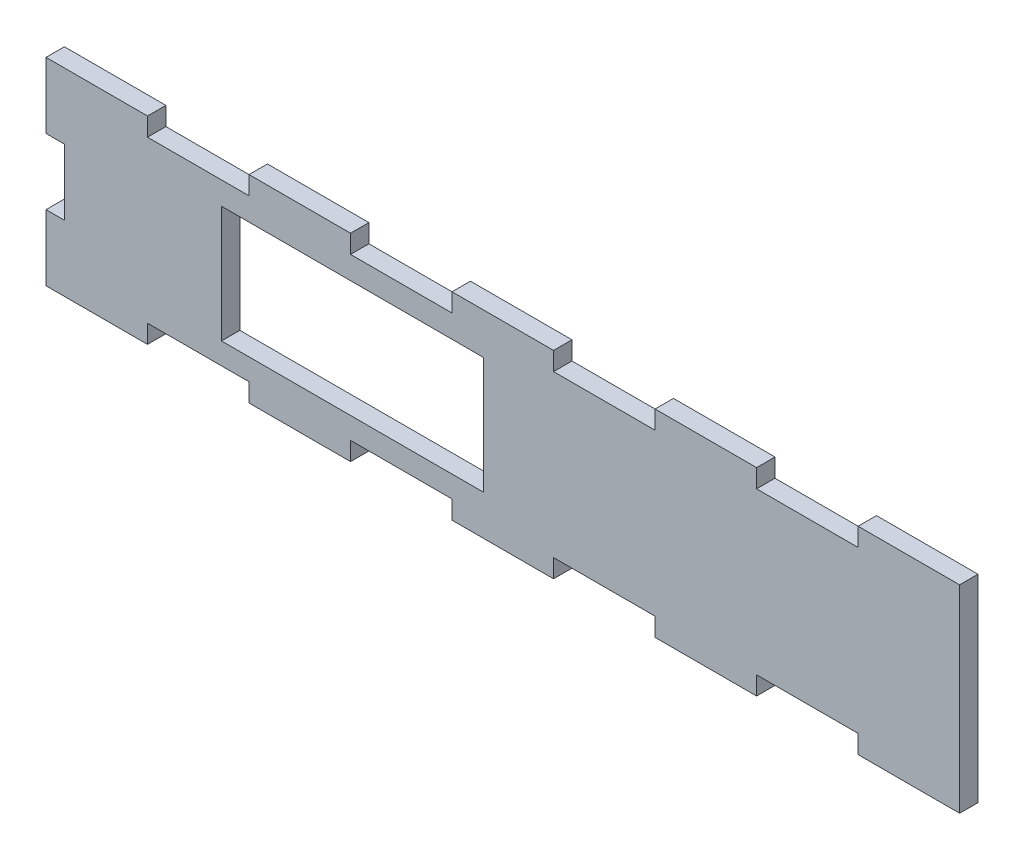
SolidWorks part; units mm, degrees
ref_plane "Front Plane" through (0, 0, 0) normal (0, 0, 1) x (1, 0, 0)
ref_plane "Top Plane" through (0, 0, 0) normal (0, 1, 0) x (1, 0, 0)
ref_plane "Right Plane" through (0, 0, 0) normal (1, 0, 0) x (0, 0, -1)
sketch "Sketch2" plane through (0, 0, 0) normal (0, 0, 1) x (1, 0, 0)
  line L1 (0, 0) -> (228.6, 0)
  line L2 (0, 0) -> (0, 49.5)
  line L3 (0, 49.5) -> (228.6, 49.5)
  line L4 (228.6, 0) -> (228.6, 49.5)
  line L5 (0, 0) -> (228.6, 49.5) construction
  line L6 (0, 49.5) -> (228.6, 0) construction
  point P4 (114.3, 24.75)
  dimension "D1" = 228.6
  dimension "D2" = 49.5
extrude "Boss-Extrude1" add sketch "Sketch2" along normal blind 4.6
sketch "Sketch4" plane through (0, 0, 4.6) normal (0, 0, 1) x (1, 0, 0)
  line L0 (0, 0) -> (228.6, 0) construction
  line L1 (25.4, 0) -> (50.8, 0)
  line L2 (25.4, 0) -> (25.4, 4.6)
  line L3 (25.4, 4.6) -> (50.8, 4.6)
  line L4 (50.8, 0) -> (50.8, 4.6)
  line L5 (25.4, 0) -> (50.8, 4.6) construction
  line L6 (25.4, 4.6) -> (50.8, 0) construction
  line L7 (0, 0) -> (25.4, 0) construction
  line L8 (76.2, 0) -> (101.6, 0)
  line L9 (76.2, 0) -> (76.2, 4.6)
  line L10 (76.2, 4.6) -> (101.6, 4.6)
  line L11 (101.6, 0) -> (101.6, 4.6)
  line L12 (76.2, 0) -> (101.6, 4.6) construction
  line L13 (76.2, 4.6) -> (101.6, 0) construction
  line L14 (127, 0) -> (152.4, 0)
  line L15 (127, 0) -> (127, 4.6)
  line L16 (127, 4.6) -> (152.4, 4.6)
  line L17 (152.4, 0) -> (152.4, 4.6)
  line L18 (127, 0) -> (152.4, 4.6) construction
  line L19 (127, 4.6) -> (152.4, 0) construction
  line L20 (177.8, 0) -> (203.2, 0)
  line L21 (177.8, 0) -> (177.8, 4.6)
  line L22 (177.8, 4.6) -> (203.2, 4.6)
  line L23 (203.2, 0) -> (203.2, 4.6)
  line L24 (177.8, 0) -> (203.2, 4.6) construction
  line L25 (177.8, 4.6) -> (203.2, 0) construction
  line L27 (50.8, 0) -> (76.2, 0) construction
  line L29 (101.6, 0) -> (127, 0) construction
  line L30 (152.4, 0) -> (177.8, 0) construction
  line L31 (203.2, 0) -> (228.6, 0) construction
  point P4 (38.1, 2.3)
  point P11 (88.9, 2.3)
  point P16 (139.7, 2.3)
  point P21 (190.5, 2.3)
  dimension "D1" = 25.4
  dimension "D2" = 4.6
extrude "Cut-Extrude1" cut sketch "Sketch4" against normal through all
ref_plane "Plane1" through (0, 24.75, 0) normal (0, 1, 0) x (1, 0, 0)
mirror "Mirror1" about plane through (0, 24.75, 0) normal (0, 1, 0) of "Cut-Extrude1"
sketch "Sketch5" plane through (0, 0, 0) normal (-1, 0, 0) x (0, 0, 1)
  line L0 (0, 49.5) -> (0, 0) construction
  line L1 (4.6, 49.5) -> (4.6, 0) construction
  line L2 (0, 16.5) -> (4.6, 16.5)
  line L3 (0, 16.5) -> (0, 33)
  line L4 (0, 33) -> (4.6, 33)
  line L5 (4.6, 16.5) -> (4.6, 33)
  line L6 (0, 16.5) -> (4.6, 33) construction
  line L7 (0, 33) -> (4.6, 16.5) construction
  line L8 (4.6, 49.5) -> (4.6, 33) construction
  line L9 (4.6, 16.5) -> (4.6, 0) construction
  point P6 (2.3, 24.75)
extrude "Cut-Extrude2" cut sketch "Sketch5" against normal blind 4.6
extrude "Cut-Extrude3" cut sketch "Sketch6" against normal through all
sketch "Sketch6" plane through (29.4576, -124.7153, 49.5) normal (0, 0, 1) x (1, 0, 0)
  line L2 (79.9501, 163.9153) -> (14.4501, 163.9153)
  line L3 (14.4501, 134.7153) -> (79.9501, 134.7153)
  line L4 (79.9501, 134.7153) -> (79.9501, 163.9153)
  line L5 (14.4501, 134.7153) -> (14.4501, 163.9153)
  line L6 (79.9501, 149.3153) -> (14.4501, 149.3153) construction
  point P4 (79.9501, 149.3153)
  point P5 (14.4501, 149.3153)
equation "\"MDF\"= 4.8mm"
equation "\"Foamcore\"= 4.6mm"
equation "\"PCB\" = 1.6mm"
equation "\"GMaterial\"= \"MDF\""
equation "\"BaseWidth\" = 10in"
equation "\"SkidLength\" = 1in"
equation "\"SkidClearance\" = 0.4in"
equation "\"MotorMountLength\" = 2in"
equation "\"MotorMountWidth\" = \"GMaterial\""
equation "\"MotorMountHeight\" = 2.25in"
equation "\"UnoStackWidth\" = 77.4mm"
equation "\"UnoStackLength\" = 79.8mm"
equation "\"UnoStackHeight\" = 34.2mm"
equation "\"TallHexRiserHeight\" = 22.2mm"
equation "\"PingPongBallSize\" = 40mm"
equation "\"BarrelLength\" = 9in"
equation "\"BarrelSize\" = \"PingPongBallSize\""
equation "\"D2@Sketch2\"=\"BarrelSize\"+\"Foamcore\"*2 + \"LaserCutterOffset\""
equation "\"D1@Boss-Extrude1\"=\"Foamcore\""
equation "\"D2@Sketch4\"=\"Foamcore\""
equation "\"D1@Cut-Extrude2\"=\"Foamcore\""
equation "\"PlatformLength\" = 4in"
equation "\"PlatformWidth\" = 6in"
equation "\"WheelDiameter\"=2.99213"
equation "\"ServoMountHeight\"=2.49223"
equation "\"ServoGearHeight\" = 0.95330261in"
equation "\"ServoMountLength\"= 1.53774"
equation "\"PivotHoleRadius\"= 0.616358"
equation "\"PlatformMountHeight\" = 3.19"
equation "\"TensionOffSet\"= .3mm"
equation "\"MotorMountWedge\"=0.333333"
equation "\"LaserCutterOffset\"= .3mm"
equation "\"BumperWidth\"=11"
equation "\"PitcherWheelCompression\" = 2.5mm"
equation "\"PitchingWheelWidth\" = 26.2mm"
equation "\"PitchingWheelDiameter\" = 65.5mm"
equation "\"PitchingWheelMountOffset\" = 8.4mm"
equation "\"PitchingWheelInnerDiameter\" = 45.5mm"
equation "\"PitchingWheelBoltShoulder\" = 4.5mm"
equation "\"BrassCouplingLength\" = 18mm"
equation "\"PitchingMotorHeight\" = 57.0mm"
equation "\"PitchingMotorShaftTopHeight\" = \"PitchingMotorHeight\" - 44.1mm"
equation "\"PitchingMotorBodyHeight\" = 38mm"
equation "\"PitchingMotorTopShoulderHeight\" = 40.6mm - \"PitchingMotorBodyHeight\" "
equation "\"PitchingMotorBottomShoulderHeight\" = 40.2mm - \"PitchingMotorBodyHeight\""
equation "\"PitchingMotorBottomShaftHeight\" = \"PitchingMotorHeight\" - \"PitchingMotorShaftTopHeight\" - \"PitchingMotorTopShoulderHeight\" - \"PitchingMotorBodyHeight\" - \"PitchingMotorBottomShoulderHeight\""
equation "\"PitchingMotorShaftDiameter\" = 2.2mm"
equation "\"PitchingMotorBodyDiameter\" = 27.4mm"
equation "\"PitchingMotorTopShoulderDiameter\" = 9.8mm"
equation "\"PitchingMotorBottomShoulderDiameter\" = 9.8mm"
equation "\"BrassCouplingHexSize\" = 12mm"
equation "\"BrassCouplingBoreSize\" = 3.17mm"
equation "\"PitchingMotorMountingHoleDistance\" = 16mm"
equation "\"Acrylic\" = 4.4mm"
equation "\"PitchingMotorDistance\" = \"PitchingWheelDiameter\" + \"PingPongBallSize\" - \"PitcherWheelCompression\"*2"
equation "\"PitchingMotorPlatformOffset\"=1"
equation "\"ServoPlatformOffset\"=1.64173"
equation "\"BallBearingDiameter\" = 22mm"
equation "\"BallBearingWidth\" = 9mm"
equation "\"BallBearingHexShoulder\" = 9mm - 5.9mm"
equation "\"BallBearingHexSize\" = .36in"
equation "\"PlatformMountFootLength\"=0.857143"
equation "\"WheelWidth\"= 26mm"
equation "\"ServoMountReductionBackHeight\"=2.25"
equation "\"PlatformBottomWidthThird\" =  0.857143in"
equation "\"PlatformMountBackReductionHeight\"= 2.5in"
equation "\"PlatformMountBackReductionWidth\"= 3/7in"
equation "\"PlatformMountFrontReductionWidth\" =  1.46226in"
equation "\"PlatformMountFrontReductionHeight\" = 2.5in"
